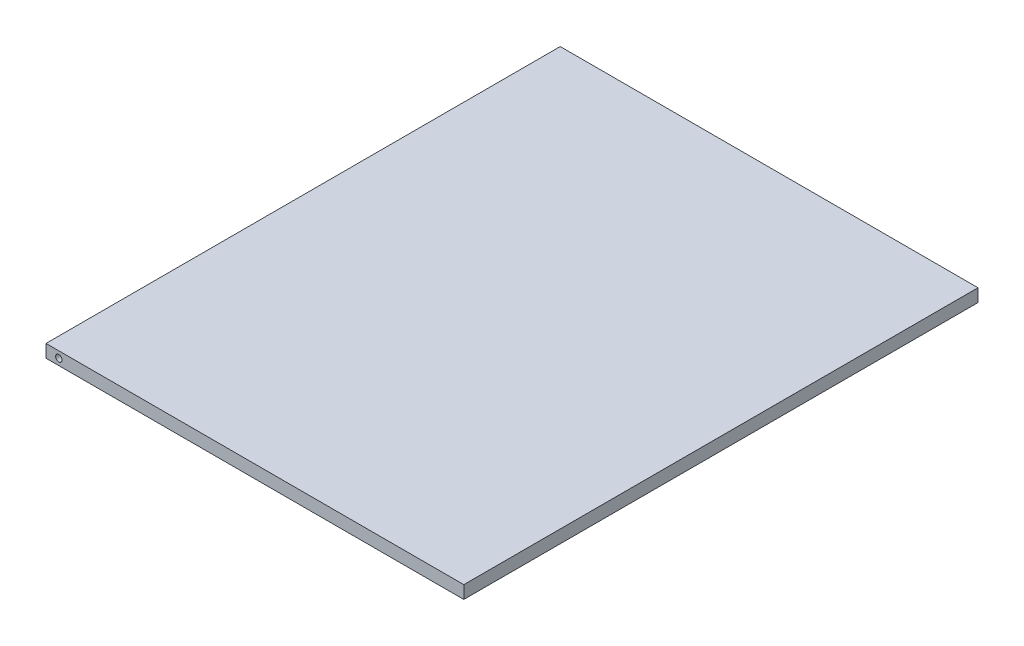
SolidWorks part; units mm, degrees
ref_plane "Front Plane" through (0, 0, 0) normal (0, 0, 1) x (1, 0, 0)
ref_plane "Top Plane" through (0, 0, 0) normal (0, 1, 0) x (1, 0, 0)
ref_plane "Right Plane" through (0, 0, 0) normal (1, 0, 0) x (0, 0, -1)
sketch "Sketch1" plane through (0, 0, 0) normal (0, 1, 0) x (1, 0, 0)
  line L1 (32.5, 40) -> (-32.5, 40)
  line L2 (32.5, 40) -> (32.5, -40)
  line L3 (32.5, -40) -> (-32.5, -40)
  line L4 (-32.5, 40) -> (-32.5, -40)
  line L5 (32.5, 40) -> (-32.5, -40) construction
  line L6 (32.5, -40) -> (-32.5, 40) construction
  point P0 (0, 0)
  dimension "D1" = 80
  dimension "D2" = 65
extrude "Boss-Extrude1" add sketch "Sketch1" along normal blind 2
sketch "Sketch2" plane through (0, 0, 40) normal (0, 0, 1) x (1, 0, 0)
  line L0 (-32.5, 2) -> (-32.5, 0) construction
  circle A0 centre (-30.5, 1) radius 0.5
  point P2 (-32.5, 1)
  dimension "D1" = 1
  dimension "D2" = 2
extrude "Cut-Extrude1" cut sketch "Sketch2" against normal through all
